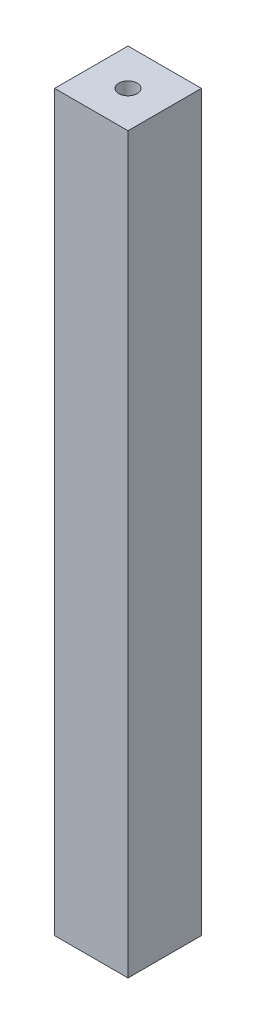
SolidWorks part; units mm, degrees
ref_plane "Front Plane" through (0, 0, 0) normal (0, 0, 1) x (1, 0, 0)
ref_plane "Top Plane" through (0, 0, 0) normal (0, 1, 0) x (1, 0, 0)
ref_plane "Right Plane" through (0, 0, 0) normal (1, 0, 0) x (0, 0, -1)
sketch "Sketch1" plane through (0, 0, 0) normal (0, 1, 0) x (1, 0, 0)
  line L1 (10, -10) -> (-10, -10)
  line L2 (10, -10) -> (10, 10)
  line L3 (10, 10) -> (-10, 10)
  line L4 (-10, -10) -> (-10, 10)
  line L5 (10, -10) -> (-10, 10) construction
  line L6 (10, 10) -> (-10, -10) construction
  point P0 (0, 0)
  dimension "D1" = 20
  dimension "D2" = 20
extrude "Boss-Extrude1" add sketch "Sketch1" along normal blind 200
sketch "Sketch2" plane through (0, 200, 0) normal (0, 1, 0) x (1, 0, 0)
  circle A0 centre (0, 0) radius 2.5
extrude "Cut-Extrude1" cut sketch "Sketch2" against normal blind 150
